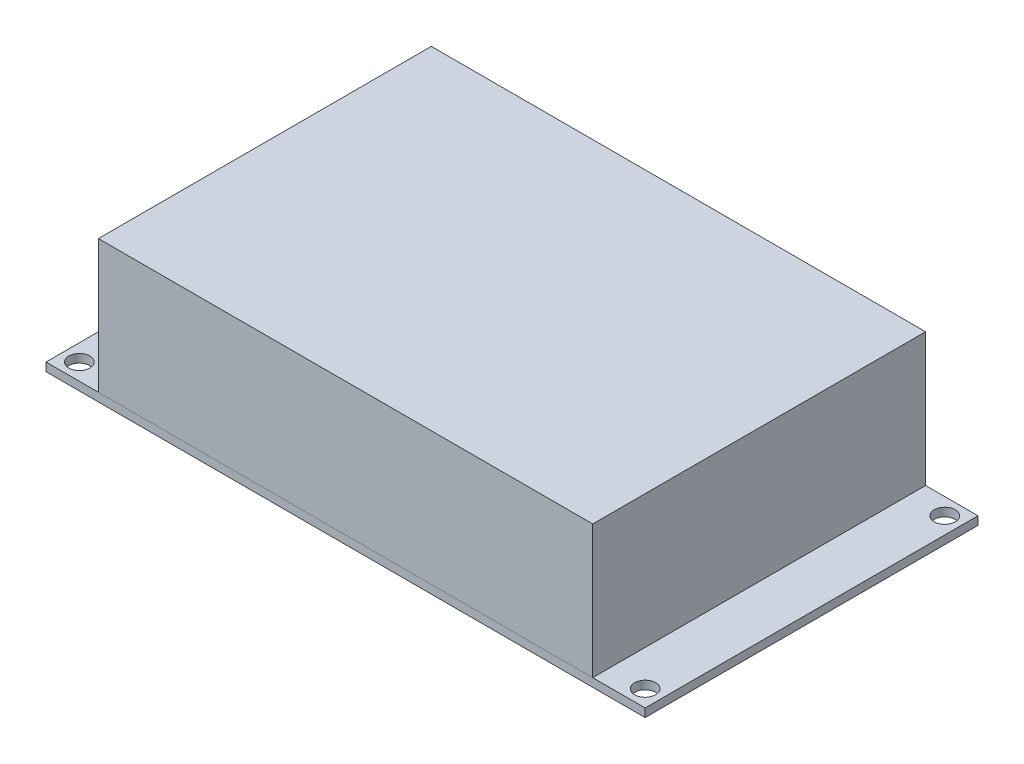
SolidWorks part; units mm, degrees
material "ABS"
ref_plane "Plan de face" through (0, 0, 0) normal (0, 0, 1) x (1, 0, 0)
ref_plane "Plan de dessus" through (0, 0, 0) normal (0, 1, 0) x (1, 0, 0)
ref_plane "Plan de droite" through (0, 0, 0) normal (1, 0, 0) x (0, 0, -1)
sketch "Esquisse1" plane through (0, 0, 0) normal (0, 1, 0) x (1, 0, 0)
  line L1 (0, 0) -> (114.3, 0)
  line L2 (0, 0) -> (0, 63.5)
  line L3 (0, 63.5) -> (114.3, 63.5)
  line L4 (114.3, 0) -> (114.3, 63.5)
  dimension "D1" = 114.3
  dimension "D2" = 63.5
extrude "Extrusion1" add sketch "Esquisse1" along normal blind 1.6
sketch "Esquisse2" plane through (0, 1.6, 0) normal (0, 1, 0) x (-1, 0, 0)
  line L0 (0, -31.75) -> (-114.3, -31.75) construction
  line L1 (0, -63.5) -> (0, 0) construction
  line L2 (-114.3, 0) -> (-114.3, -63.5) construction
  line L3 (8.5277, -60.325) -> (-123.6209, -60.325) construction
  line L4 (5.6722, -3.175) -> (-126.9524, -3.175) construction
  line L5 (-3.175, -73.2348) -> (-3.175, 10.3694) construction
  line L6 (-57.15, -63.5) -> (-57.15, 0) construction
  line L7 (-114.3, -63.5) -> (0, -63.5) construction
  line L8 (0, 0) -> (-114.3, 0) construction
  line L9 (-111.125, -72.283) -> (-111.125, 16.3978) construction
  circle A0 centre (-3.175, -60.325) radius 2
  circle A1 centre (-3.175, -3.175) radius 2
  circle A2 centre (-111.125, -60.325) radius 2
  circle A3 centre (-111.125, -3.175) radius 2
  dimension "D1" = 53.975
  dimension "D2" = 53.975
  dimension "D3" = 28.575
  dimension "D4" = 28.575
extrude "Enlèv. mat.-Extru.1" cut sketch "Esquisse2" against normal blind 1.6
sketch "Esquisse3" plane through (0, 0, 0) normal (0, -1, 0) x (1, 0, 0)
  line L4 (0, 0) -> (0, -63.5)
  line L5 (0, -63.5) -> (114.3, -63.5)
  line L6 (114.3, -63.5) -> (114.3, 0)
  line L7 (114.3, 0) -> (0, 0)
  line L8 (0, 0) -> (0, -63.5)
  line L9 (0, -63.5) -> (114.3, -63.5)
  line L10 (114.3, -63.5) -> (114.3, 0)
  line L11 (114.3, 0) -> (0, 0)
  dimension "D1" = 0
extrude "Extrusion3" [suppressed] add sketch "Esquisse3" along normal blind 3.5 separate body
sketch "Esquisse4" plane through (0, 1.6, 0) normal (0, 1, 0) x (-1, 0, 0)
  line L0 (-104.3, -63.5) -> (-104.3, 0)
  line L1 (-10, -63.5) -> (-10, 0)
  line L4 (0, -63.5) -> (0, 0)
  line L5 (0, 0) -> (-114.3, 0)
  line L6 (-114.3, 0) -> (-114.3, -63.5)
  line L7 (-114.3, -63.5) -> (0, -63.5)
  line L9 (-10, 0) -> (-104.3, 0)
  line L11 (-104.3, -63.5) -> (-10, -63.5)
  dimension "D1" = 0
extrude "Extrusion4" add sketch "Esquisse4" along normal blind 25.4 separate body
